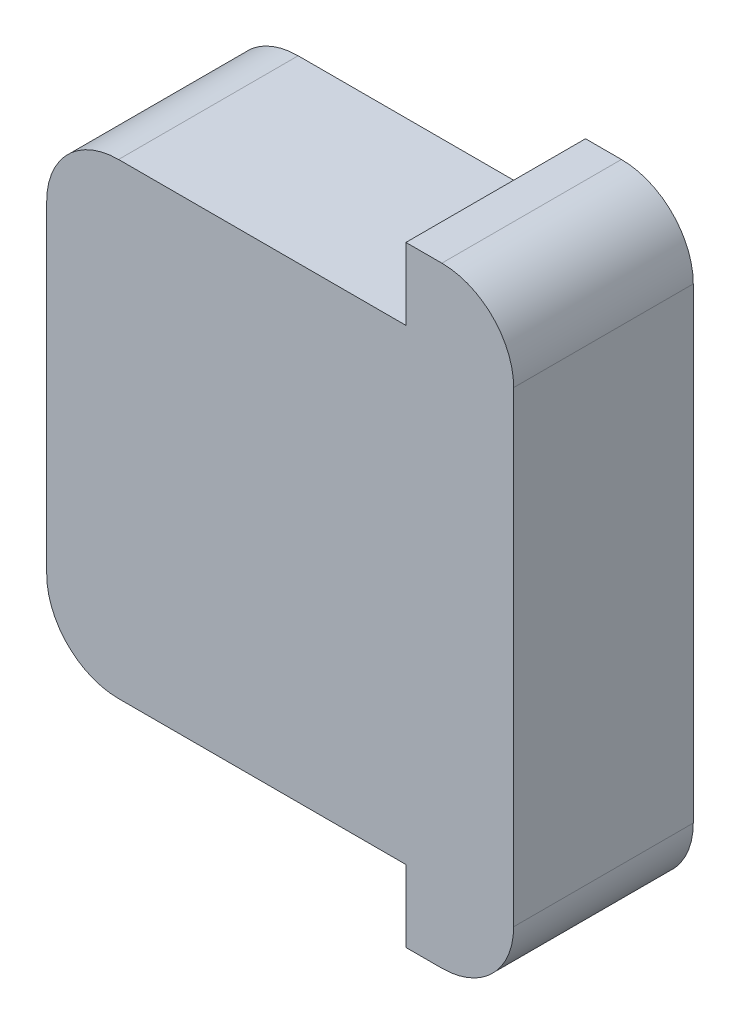
SolidWorks part; units mm, degrees
ref_plane "Plan de face" through (0, 0, 0) normal (0, 0, 1) x (1, 0, 0)
ref_plane "Plan de dessus" through (0, 0, 0) normal (0, 1, 0) x (1, 0, 0)
ref_plane "Plan de droite" through (0, 0, 0) normal (1, 0, 0) x (0, 0, -1)
sketch "Esquisse1" plane through (0, 0, 0) normal (0, 0, 1) x (1, 0, 0)
  line L0 (0, 6.5) -> (0, 8.5)
  line L1 (-10, 6.5) -> (0, 6.5)
  line L2 (-10, 6.5) -> (-10, -6.5)
  line L3 (-10, -6.5) -> (0, -6.5)
  line L4 (0, 6.5) -> (0, -6.5) construction
  line L5 (0, 8.5) -> (3, 8.5)
  line L6 (3, 8.5) -> (3, -8.5)
  line L7 (3, -8.5) -> (0, -8.5)
  line L8 (0, -8.5) -> (0, -6.5)
  line L9 (0, 0) -> (-10, 0) construction
  point P11 (0, 0)
  point P12 (3, 7.3565)
  dimension "D1" = 13
  dimension "D2" = 17
  dimension "D3" = 2
  dimension "D4" = 10
  dimension "D5" = 3
extrude "Boss.-Extru.1" add sketch "Esquisse1" along normal blind 5
fillet "Congé1" radius 2 4 edges at (-10, -6.5, 2.5) (3, -8.5, 2.5) (3, 8.5, 2.5) (-10, 6.5, 2.5)
